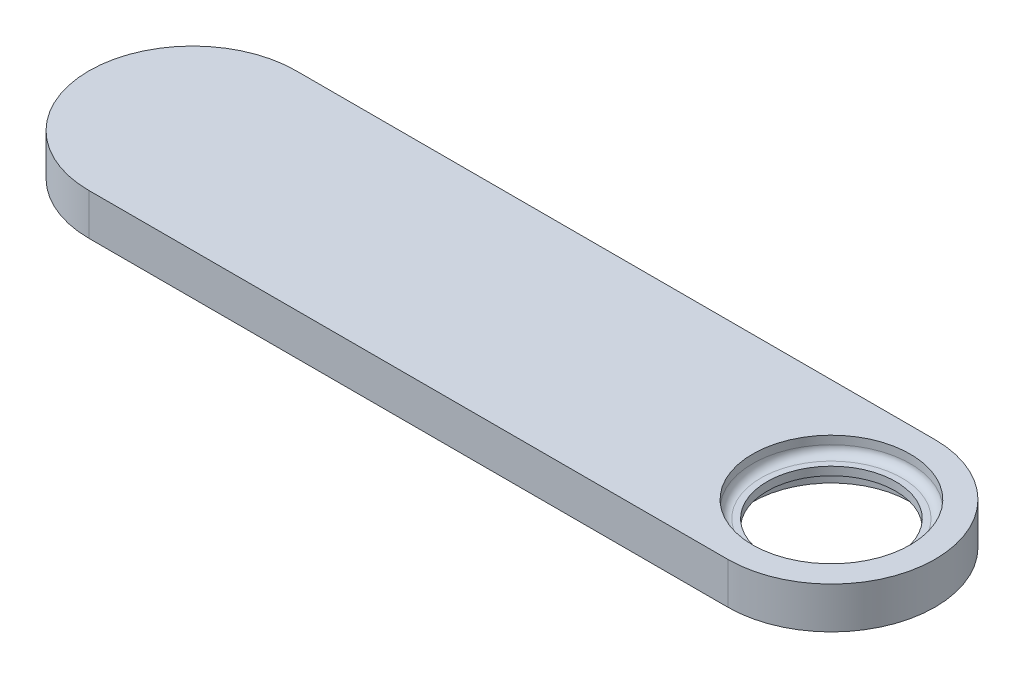
SolidWorks part; units mm, degrees
ref_plane "前视基准面" through (0, 0, 0) normal (0, 0, 1) x (1, 0, 0)
ref_plane "上视基准面" through (0, 0, 0) normal (0, 1, 0) x (1, 0, 0)
ref_plane "右视基准面" through (0, 0, 0) normal (1, 0, 0) x (0, 0, -1)
sketch "草图1" plane through (0, 0, 0) normal (0, 1, 0) x (1, 0, 0)
  line L0 (-38.5204, 0) -> (38.5204, 0) construction
  line L1 (-38.5204, 12.5) -> (38.5204, 12.5)
  line L2 (-38.5204, -12.5) -> (38.5204, -12.5)
  arc A0 (-38.5204, 12.5) -> (-38.5204, -12.5) centre (-38.5204, 0) ccw
  arc A1 (38.5204, -12.5) -> (38.5204, 12.5) centre (38.5204, 0) ccw
  point P2 (0, 0)
  dimension "D1" = 12.5
extrude "凸台-拉伸1" add sketch "草图1" along normal blind 5
sketch "草图2" plane through (0, 5, 0) normal (0, 1, 0) x (1, 0, 0)
  circle A0 centre (38.5204, 0) radius 7.75
  dimension "D1" = 15.5
extrude "切除-拉伸1" cut sketch "草图2" against normal up to next
sketch "草图3" plane through (0, 5, 0) normal (0, 1, 0) x (1, 0, 0)
  circle A0 centre (38.5204, 0) radius 9.5
  dimension "D1" = 19
extrude "切除-拉伸2" cut sketch "草图3" against normal blind 2
sketch "草图4" plane through (0, 0, 0) normal (0, -1, 0) x (1, 0, 0)
  circle A0 centre (38.5204, 0) radius 9.5
  dimension "D1" = 19
extrude "切除-拉伸3" cut sketch "草图4" against normal blind 2
fillet "圆角1" radius 1 2 edges at (38.5204, 3, 9.5) (38.5204, 2, -9.5)
